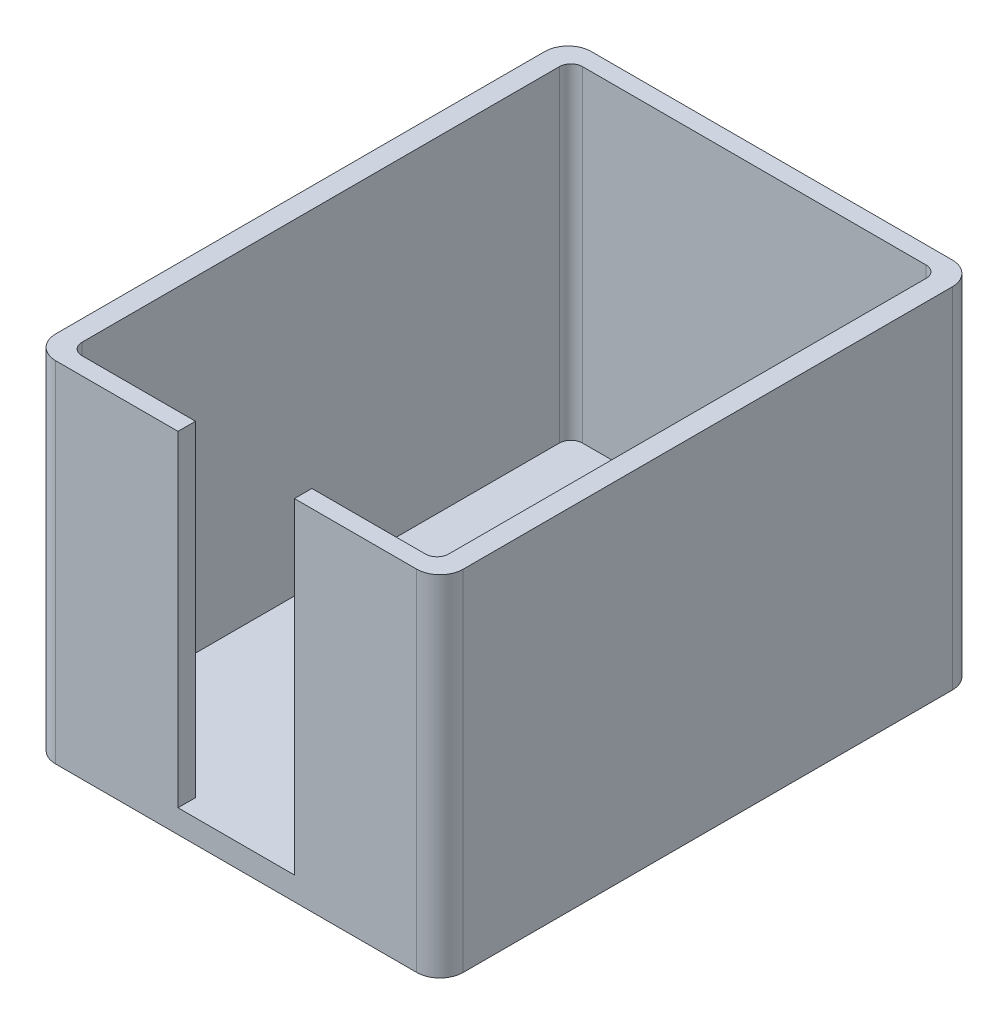
SolidWorks part; units mm, degrees
ref_plane "Front Plane" through (0, 0, 0) normal (0, 0, 1) x (1, 0, 0)
ref_plane "Top Plane" through (0, 0, 0) normal (0, 1, 0) x (1, 0, 0)
ref_plane "Right Plane" through (0, 0, 0) normal (1, 0, 0) x (0, 0, -1)
sketch "Sketch1" plane through (0, 0, 0) normal (0, 1, 0) x (1, 0, 0)
  line L1 (-17.5, 23) -> (17.5, 23)
  line L2 (-17.5, 23) -> (-17.5, -23)
  line L3 (-17.5, -23) -> (17.5, -23)
  line L4 (17.5, 23) -> (17.5, -23)
  line L5 (-17.5, 23) -> (17.5, -23) construction
  line L6 (-17.5, -23) -> (17.5, 23) construction
  point P0 (0, 0)
  dimension "D1" = 46
  dimension "D2" = 35
extrude "Boss-Extrude1" add sketch "Sketch1" along normal blind 30
sketch "Sketch2" plane through (0, 30, 0) normal (0, 1, 0) x (1, 0, 0)
  line L1 (-15.75, 21.5) -> (15.75, 21.5)
  line L2 (-15.75, 21.5) -> (-15.75, -21.5)
  line L3 (-15.75, -21.5) -> (15.75, -21.5)
  line L4 (15.75, 21.5) -> (15.75, -21.5)
  line L5 (-15.75, 21.5) -> (15.75, -21.5) construction
  line L6 (-15.75, -21.5) -> (15.75, 21.5) construction
  point P0 (0, 0)
  dimension "D1" = 43
  dimension "D2" = 31.5
extrude "Cut-Extrude1" cut sketch "Sketch2" against normal blind 28
fillet "Fillet1" radius 2 4 edges at (-17.5, 15, -23) (17.5, 15, -23) (17.5, 15, 23) (-17.5, 15, 23)
fillet "Fillet2" radius 1 4 edges at (-15.75, 16, -21.5) (-15.75, 16, 21.5) (15.75, 16, 21.5) (15.75, 16, -21.5)
sketch "Sketch3" plane through (0, 0, 23) normal (0, 0, 1) x (1, 0, 0)
  line L0 (-15.5, 30) -> (15.5, 30) construction
  line L1 (5, 30) -> (-5, 30)
  line L2 (5, 30) -> (5, 2)
  line L3 (5, 2) -> (-5, 2)
  line L4 (-5, 30) -> (-5, 2)
  line L5 (-15.5, 30) -> (-15.5, 0) construction
  dimension "D1" = 10
  dimension "D2" = 10.5
  dimension "D3" = 28
extrude "Cut-Extrude2" cut sketch "Sketch3" against normal blind 8
